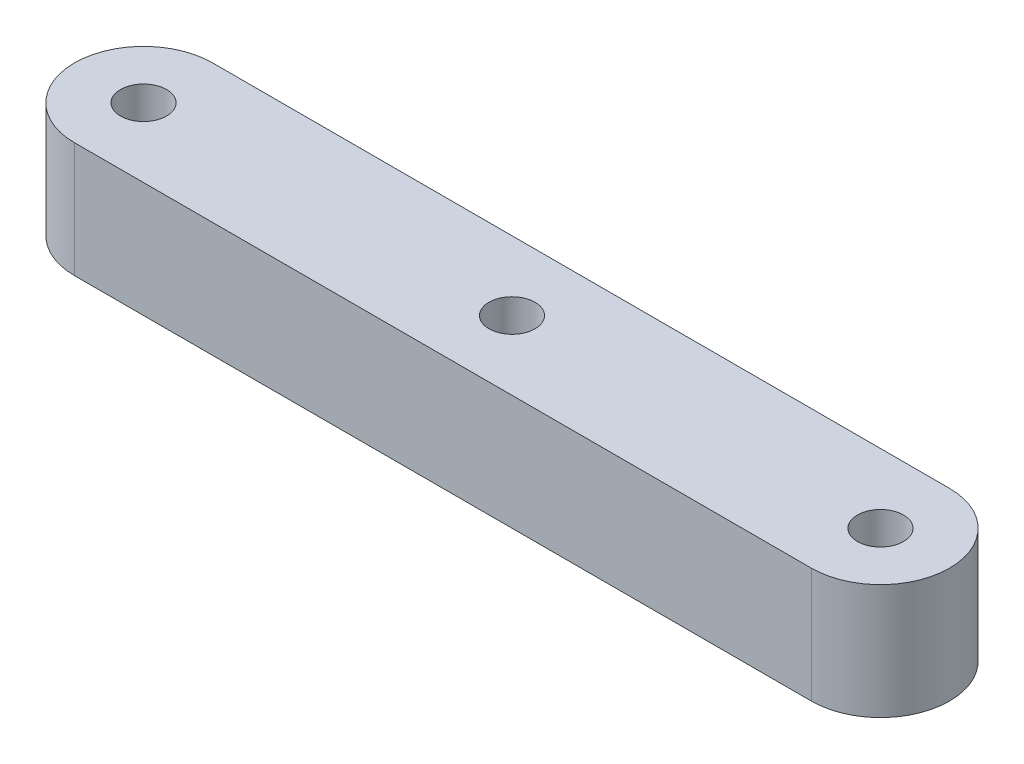
SolidWorks part; units mm, degrees
ref_plane "Front Plane" through (0, 0, 0) normal (0, 0, 1) x (1, 0, 0)
ref_plane "Top Plane" through (0, 0, 0) normal (0, 1, 0) x (1, 0, 0)
ref_plane "Right Plane" through (0, 0, 0) normal (1, 0, 0) x (0, 0, -1)
sketch "Sketch3" plane through (0, 0, 0) normal (0, 1, 0) x (1, 0, 0)
  line L0 (-50.8, 0) -> (30.48, 0) construction
  line L1 (-6.985, 0) -> (6.985, 0) construction
  line L2 (-50.8, 7.62) -> (30.48, 7.62)
  line L3 (-50.8, -7.62) -> (30.48, -7.62)
  arc A0 (-50.8, 7.62) -> (-50.8, -7.62) centre (-50.8, 0) ccw
  arc A1 (30.48, -7.62) -> (30.48, 7.62) centre (30.48, 0) ccw
  point P5 (-10.16, 0)
  point P10 (0, 0)
  point P11 (0, 0)
  point P12 (0, 0)
  point P13 (0, 0)
  point P14 (0, 0)
  dimension "D2" = 7.62
  dimension "D1" = 81.28
  dimension "D3" = 50.8
extrude "Boss-Extrude1" add sketch "Sketch3" along normal blind 12.7
sketch "Sketch4" plane through (0, 12.7, 0) normal (0, 1, 0) x (1, 0, 0)
  circle A0 centre (-50.8, 0) radius 2.54
  circle A1 centre (30.48, 0) radius 2.54
  circle A3 centre (-10.16, 0) radius 2.54
  dimension "D1" = 5.08
extrude "Cut-Extrude3" cut sketch "Sketch4" against normal through all
equation "\"TibiaLength\"= 4in"
equation "\"TibiaRadius\"= 0.3in"
equation "\"TibiaDistFromCentre\"= \"TibiaLength\" / 2"
equation "\"TibiaThickness\"= 0.5in"
equation "\"HoleRadius\"= 0.2in"
equation "\"D1@Sketch3\"= \"TibiaLength\" * 0.8"
equation "\"D2@Sketch3\"= \"TibiaRadius\""
equation "\"D3@Sketch3\"= \"TibiaDistFromCentre\""
equation "\"D1@Boss-Extrude1\"= \"TibiaThickness\""
equation "\"D1@Sketch4\"= \"HoleRadius\""
